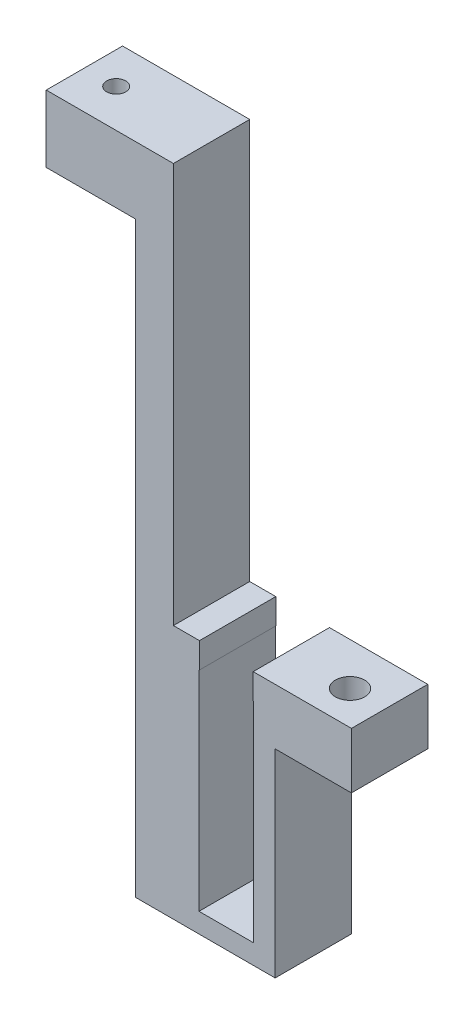
SolidWorks part; units mm, degrees
ref_plane "Front Plane" through (0, 0, 0) normal (0, 0, 1) x (1, 0, 0)
ref_plane "Top Plane" through (0, 0, 0) normal (0, 1, 0) x (1, 0, 0)
ref_plane "Right Plane" through (0, 0, 0) normal (1, 0, 0) x (0, 0, -1)
sketch "Sketch1" plane through (0, 0, 0) normal (0, 0, 1) x (1, 0, 0)
  line L1 (-9.6863, 12.1914) -> (-1.6863, 12.1914)
  line L2 (-9.6863, 12.1914) -> (-9.6863, -7.8086)
  line L3 (-9.6863, -7.8086) -> (-1.6863, -7.8086)
  line L4 (-1.6863, 12.1914) -> (-1.6863, -7.8086)
  dimension "D1" = 8
  dimension "D2" = 20
extrude "Boss-Extrude1" add sketch "Sketch1" along normal blind 6
sketch "Sketch2" plane through (0, 0, 6) normal (0, 0, 1) x (1, 0, 0)
  line L1 (-3.3863, 10.1914) -> (-7.6754, 10.1914)
  line L2 (-3.3863, 10.1914) -> (-3.3863, -6.2602)
  line L3 (-3.3863, -6.2602) -> (-7.6754, -6.2602)
  line L4 (-7.6754, 10.1914) -> (-7.6754, -6.2602)
extrude "Cut-Extrude1" cut sketch "Sketch2" against normal blind 10
sketch "Sketch3" plane through (0, 12.1914, 0) normal (0, 1, 0) x (1, 0, 0)
  line L0 (-1.6863, 0) -> (-9.6863, 0) construction
  line L1 (-7.6371, 0) -> (-3.4145, 0)
  line L2 (-7.6371, 0) -> (-7.6371, -6)
  line L3 (-7.6371, -6) -> (-3.4145, -6)
  line L4 (-3.4145, 0) -> (-3.4145, -6)
  line L5 (-1.6863, -6) -> (-9.6863, -6) construction
extrude "Cut-Extrude2" cut sketch "Sketch3" against normal up to next
sketch "Sketch4" plane through (-1.6863, 0, 0) normal (1, 0, 0) x (0, 0, -1)
  line L0 (0, -7.8086) -> (0, 12.1914) construction
  line L1 (-6, 12.1914) -> (0, 12.1914)
  line L2 (-6, 12.1914) -> (-6, 7.7961)
  line L3 (-6, 7.7961) -> (0, 7.7961)
  line L4 (0, 12.1914) -> (0, 7.7961)
extrude "Boss-Extrude2" add sketch "Sketch4" along normal blind 3
sketch "Sketch5" plane through (-9.6863, 0, 0) normal (-1, 0, 0) x (0, 0, 1)
  line L1 (0, -7.8086) -> (6, -7.8086)
  line L2 (0, -7.8086) -> (0, 43.661)
  line L3 (0, 43.661) -> (6, 43.661)
  line L4 (6, -7.8086) -> (6, 43.661)
extrude "Boss-Extrude3" add sketch "Sketch5" along normal blind 3
sketch "Sketch6" plane through (-12.6863, 0, 0) normal (-1, 0, 0) x (0, 0, 1)
  line L0 (6, -7.8086) -> (6, 43.661) construction
  line L1 (0, 43.661) -> (6, 43.661)
  line L2 (0, 43.661) -> (0, 38.3891)
  line L3 (0, 38.3891) -> (6, 38.3891)
  line L4 (6, 43.661) -> (6, 38.3891)
extrude "Boss-Extrude4" add sketch "Sketch6" along normal blind 7
ref_plane "Plane1" through (-19.6863, 43.661, 6) normal (1, 0, 0) x (0, 0, -1)
sketch "Sketch8" plane through (0, 43.661, 0) normal (0, 1, 0) x (1, 0, 0)
  line L0 (-19.6863, -8.75) -> (-19.6863, -3.25) construction
  line L1 (-19.6863, 0) -> (-9.6863, 0) construction
  circle A0 centre (-17.1863, -3) radius 0.75
  dimension "D1" = 2.5
  dimension "D2" = 3
extrude "Cut-Extrude3" cut sketch "Sketch8" against normal through all
sketch "Sketch9" plane through (1.3137, 0, 0) normal (1, 0, 0) x (0, 0, -1)
  line L1 (-6, 12.1914) -> (0, 12.1914)
  line L2 (-6, 12.1914) -> (-6, 7.7961)
  line L3 (-6, 7.7961) -> (0, 7.7961)
  line L4 (0, 12.1914) -> (0, 7.7961)
extrude "Boss-Extrude5" add sketch "Sketch9" along normal blind 3
sketch "Sketch10" plane through (0, 12.1914, 0) normal (0, 1, 0) x (1, 0, 0)
  circle A0 centre (1.5395, -3.3367) radius 1.15
extrude "Cut-Extrude4" cut sketch "Sketch10" against normal through all
